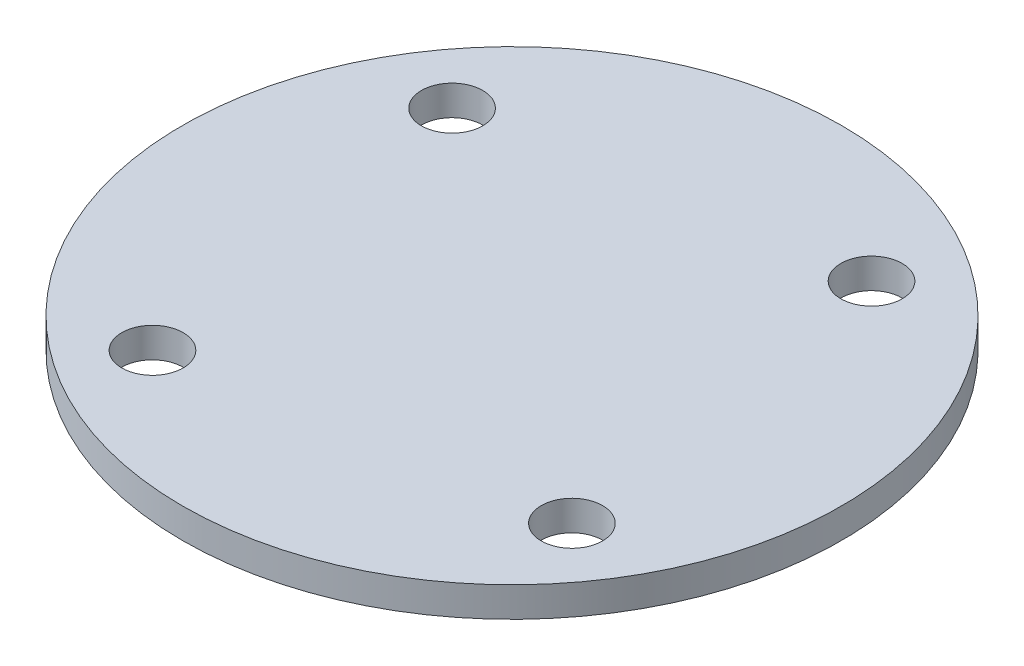
SolidWorks part; units mm, degrees
ref_plane "Front Plane" through (0, 0, 0) normal (0, 0, 1) x (1, 0, 0)
ref_plane "Top Plane" through (0, 0, 0) normal (0, 1, 0) x (1, 0, 0)
ref_plane "Right Plane" through (0, 0, 0) normal (1, 0, 0) x (0, 0, -1)
sketch "Sketch1" plane through (0, 0, 0) normal (0, 1, 0) x (1, 0, 0)
  circle A0 centre (0, 0) radius 27.94
  dimension "D1" = 55.88
extrude "Boss-Extrude1" add sketch "Sketch1" along normal blind 2.54
sketch "Sketch2" plane through (0, 2.54, 0) normal (0, 1, 0) x (1, 0, 0)
  circle A0 centre (0, 0) radius 27.94 construction
  circle A1 centre (-12.7, -17.78) radius 2.6
  point P0 (-12.7, -17.78)
  dimension "D2" = 5.2
  dimension "D1" = 17.78
  dimension "D3" = 12.7
extrude "Cut-Extrude1" cut sketch "Sketch2" against normal through all
pattern_circular "CirPattern1" count 4 over 360 about axis through (0, 0, 0) along (0, 1, 0) of "Cut-Extrude1"
